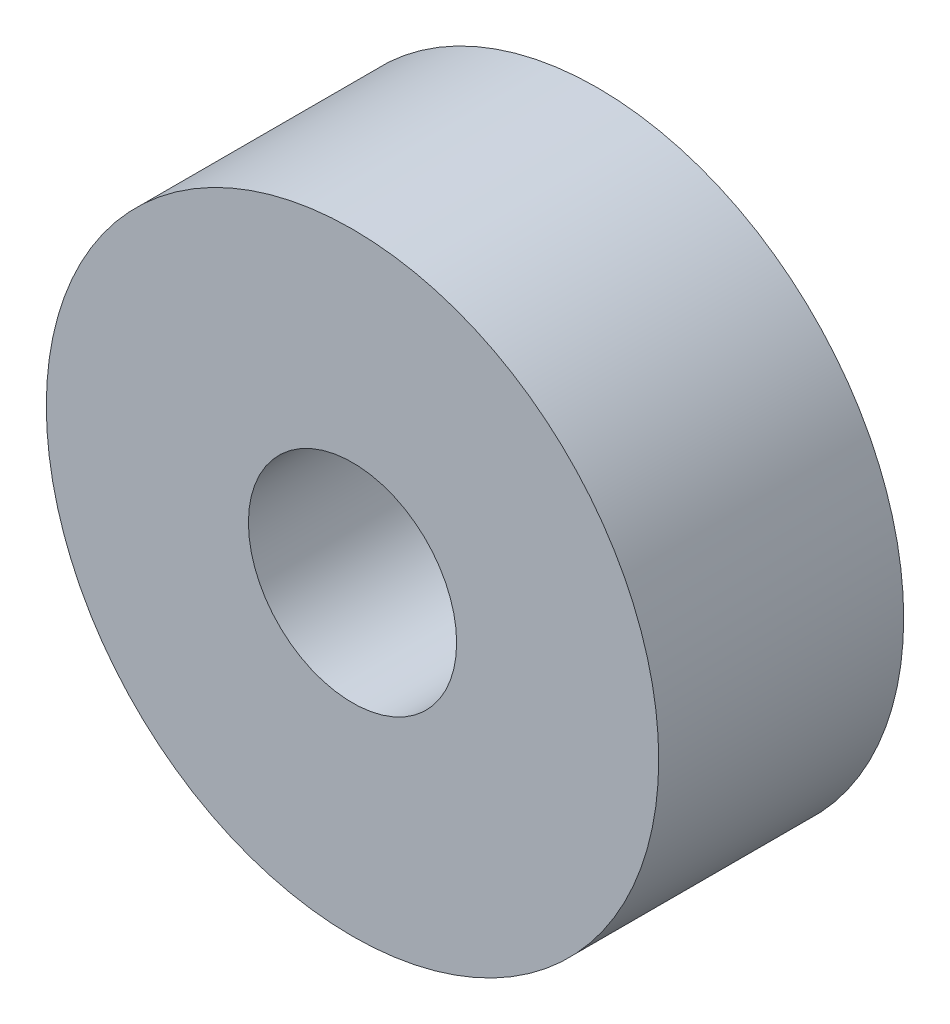
SolidWorks part; units mm, degrees
ref_plane "Front Plane" through (0, 0, 0) normal (0, 0, 1) x (1, 0, 0)
ref_plane "Top Plane" through (0, 0, 0) normal (0, 1, 0) x (1, 0, 0)
ref_plane "Right Plane" through (0, 0, 0) normal (1, 0, 0) x (0, 0, -1)
sketch "Sketch1" plane through (0, 0, 0) normal (0, 0, 1) x (1, 0, 0)
  circle A0 centre (0, 0) radius 1.7
  circle A1 centre (0, 0) radius 5
  dimension "D1" = 3.4
  dimension "D2" = 10
extrude "Boss-Extrude1" add sketch "Sketch1" along normal blind 4
